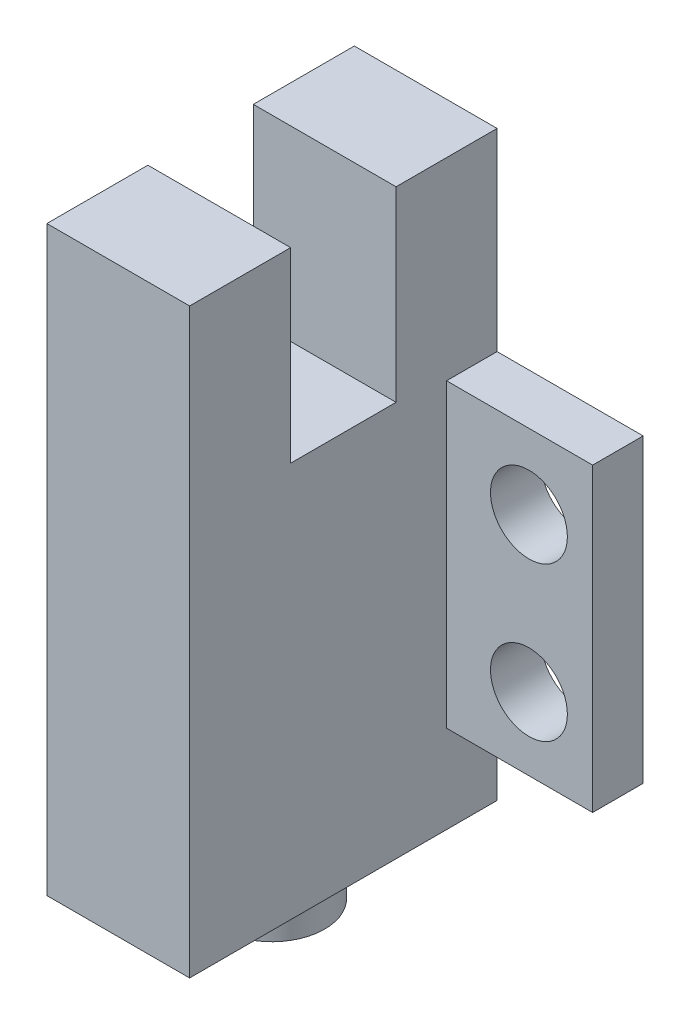
SolidWorks part; units mm, degrees
ref_plane "前视基准面" through (0, 0, 0) normal (0, 0, 1) x (1, 0, 0)
ref_plane "上视基准面" through (0, 0, 0) normal (0, 1, 0) x (1, 0, 0)
ref_plane "右视基准面" through (0, 0, 0) normal (1, 0, 0) x (0, 0, -1)
sketch "草图1" plane through (0, 0, 0) normal (0, 1, 0) x (1, 0, 0)
  line L1 (0, 0) -> (6.5, 0)
  line L2 (0, 0) -> (0, 14)
  line L3 (0, 14) -> (6.5, 14)
  line L4 (6.5, 0) -> (6.5, 14)
  dimension "D1" = 14
  dimension "D2" = 6.5
extrude "凸台-拉伸1" add sketch "草图1" along normal blind 26.5
sketch "草图2" plane through (0, 26.5, 0) normal (0, 1, 0) x (1, 0, 0)
  line L1 (0, 9.4) -> (6.5, 9.4)
  line L2 (0, 9.4) -> (0, 4.6)
  line L3 (0, 4.6) -> (6.5, 4.6)
  line L4 (6.5, 9.4) -> (6.5, 4.6)
  line L6 (0, 14) -> (0, 0) construction
  line L7 (6.5, 0) -> (6.5, 14) construction
  line L8 (0, 0) -> (6.5, 0) construction
  dimension "D1" = 4.8
  dimension "D2" = 6.5
  dimension "D3" = 4.6
extrude "切除-拉伸1" cut sketch "草图2" against normal blind 8.5
sketch "草图3" plane through (6.5, 0, 0) normal (1, 0, 0) x (0, 0, -1)
  line L0 (14, 26.5) -> (14, 0) construction
  line L1 (14, 17.7) -> (11.7, 17.7)
  line L2 (14, 17.7) -> (14, 4)
  line L3 (14, 4) -> (11.7, 4)
  line L4 (11.7, 17.7) -> (11.7, 4)
  line L5 (0, 0) -> (14, 0) construction
  dimension "D1" = 13.7
  dimension "D2" = 2.3
  dimension "D3" = 4
extrude "凸台-拉伸2" add sketch "草图3" along normal blind 6.65
sketch "草图4" plane through (0, 0, -11.7) normal (0, 0, 1) x (1, 0, 0)
  line L0 (13.15, 10.85) -> (-1.7131, 10.85) construction
  line L1 (13.15, 17.7) -> (13.15, 4) construction
  line L2 (3.25, 26.5) -> (3.25, 0.9396) construction
  line L3 (0, 26.5) -> (6.5, 26.5) construction
  line L4 (10.25, 19.0691) -> (10.25, -0.4051) construction
  line L5 (13.15, 4) -> (6.5, 4) construction
  circle A0 centre (10.25, 14.3) radius 1.75
  circle A1 centre (10.25, 7.3) radius 1.75
  dimension "D2" = 3.5
  dimension "D3" = 3.5
  dimension "D1" = 7
  dimension "D4" = 7
  dimension "D5" = 3.3
extrude "切除-拉伸2" cut sketch "草图4" against normal blind 6.65
sketch "草图5" plane through (0, 0, 0) normal (0, -1, 0) x (1, 0, 0)
  line L0 (0, 0) -> (6.5, 0) construction
  circle A0 centre (3.25, -7) radius 2.4
  dimension "D1" = 4.8
  dimension "D2" = 7
  dimension "D3" = 3.25
extrude "凸台-拉伸3" add sketch "草图5" along normal blind 2
